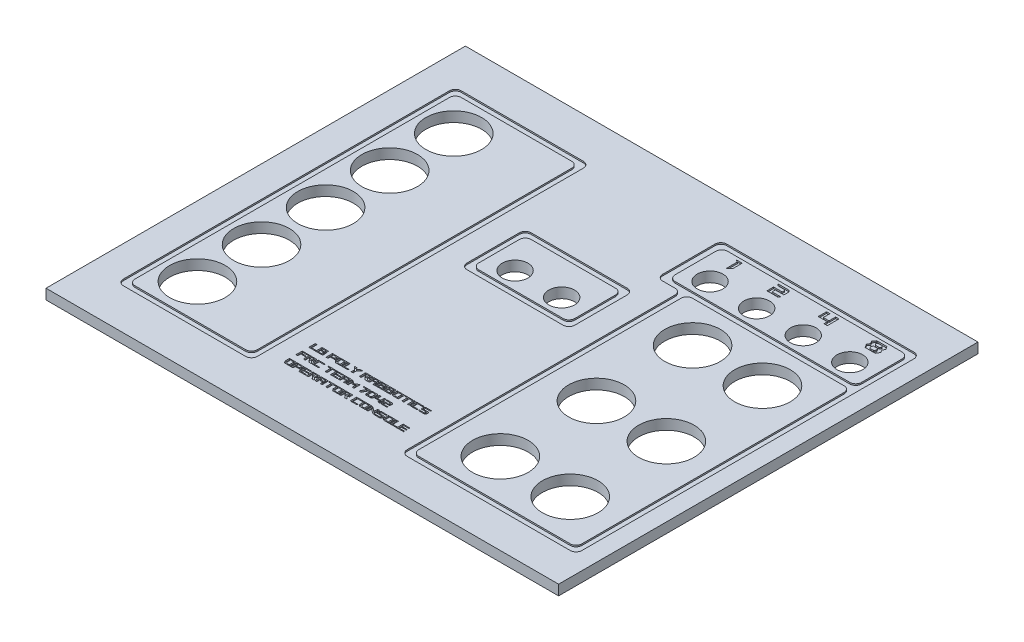
SolidWorks part; units mm, degrees
ref_plane "Front Plane" through (0, 0, 0) normal (0, 0, 1) x (1, 0, 0)
ref_plane "Top Plane" through (0, 0, 0) normal (0, 1, 0) x (1, 0, 0)
ref_plane "Right Plane" through (0, 0, 0) normal (1, 0, 0) x (0, 0, -1)
sketch "Sketch1" plane through (0, 0, 0) normal (0, 1, 0) x (1, 0, 0)
  line L1 (139.7, 114.3) -> (-139.7, 114.3)
  line L2 (139.7, 114.3) -> (139.7, -114.3)
  line L3 (139.7, -114.3) -> (-139.7, -114.3)
  line L4 (-139.7, 114.3) -> (-139.7, -114.3)
  line L5 (0, -114.3) -> (0, 114.3) construction
  line L6 (139.7, 0) -> (-139.7, 0) construction
  point P0 (0, 0)
  dimension "D1" = 279.4
  dimension "D2" = 228.6
extrude "Boss-Extrude1" add sketch "Sketch1" along normal blind 5.5562
sketch "Sketch2" plane through (0, 5.5562, 0) normal (0, 1, 0) x (1, 0, 0)
  line L1 (-139.7, 114.3) -> (-139.7, -114.3) construction
  circle A0 centre (-101.6, 69.85) radius 15.1606
  circle A3 centre (-101.6, 34.925) radius 15.1606
  circle A4 centre (-101.6, 0) radius 15.1606
  circle A5 centre (-101.6, -34.925) radius 15.1606
  circle A6 centre (-101.6, -69.85) radius 15.1606
  point P15 (-139.7, 0)
  dimension "D1" = 5
  dimension "D2" = 30.3213
  dimension "D3" = 34.925
  dimension "D4" = 38.1
extrude "Cut-Extrude1" cut sketch "Sketch2" against normal through all
sketch "Sketch3" plane through (0, 5.5562, 0) normal (0, 1, 0) x (1, 0, 0)
  line L0 (-101.6, 69.85) -> (38.1, 69.85) construction
  line L1 (-101.6, 34.925) -> (63.5, 34.925) construction
  line L2 (139.7, -114.3) -> (139.7, 114.3) construction
  line L3 (101.6, 34.925) -> (101.6, -17.4625) construction
  line L4 (-101.6, -85.0106) -> (63.5, -85.0106) construction
  circle A0 centre (38.1, 69.85) radius 7.0247
  circle A1 centre (63.5, 69.85) radius 7.0247
  circle A2 centre (88.9, 69.85) radius 7.0247
  circle A3 centre (114.3, 69.85) radius 7.0247
  circle A6 centre (63.5, 34.925) radius 15.1606
  circle A7 centre (101.6, 34.925) radius 15.1606
  circle A8 centre (-101.6, -69.85) radius 15.1606 construction
  circle A10 centre (101.6, -17.4625) radius 15.1606
  circle A11 centre (63.5, -17.4625) radius 15.1606
  circle A12 centre (101.6, -69.85) radius 15.1606
  circle A13 centre (63.5, -69.85) radius 15.1606
  dimension "D1" = 14.0494
  dimension "D5" = 38.1
  dimension "D6" = 30.3213
  dimension "D3" = 12.7
  dimension "D4" = 25.4
  dimension "D7" = 38.1
  dimension "D2" = 4
  dimension "D8" = 3
extrude "Cut-Extrude2" cut sketch "Sketch3" against normal through all
sketch "Sketch4" plane through (0, 5.5562, 0) normal (0, 1, 0) x (1, 0, 0)
  line L0 (-49.9269, -92.075) -> (-122.9519, -92.075)
  line L1 (-53.1019, -88.9) -> (-119.7769, -88.9)
  line L3 (-53.1019, 88.9) -> (-119.7769, 88.9)
  line L4 (-119.7769, -88.9) -> (-119.7769, 88.9)
  line L5 (-86.4394, 88.9) -> (-86.4394, -88.9) construction
  line L6 (-53.1019, 0) -> (-119.7769, 0) construction
  line L7 (-122.9519, -92.075) -> (-122.9519, 92.075)
  line L8 (-49.9269, 92.075) -> (-122.9519, 92.075)
  line L9 (-49.9269, -92.075) -> (-49.9269, 92.075)
  line L10 (38.1, 57.15) -> (127, -92.075) construction
  line L12 (38.1, 57.15) -> (38.1, -92.075)
  line L13 (38.1, -92.075) -> (127, -92.075)
  line L14 (127, 57.15) -> (127, -92.075)
  line L15 (63.5, -17.4625) -> (101.6, -17.4625) construction
  line L17 (130.175, 60.325) -> (130.175, -95.25)
  line L18 (34.925, -95.25) -> (130.175, -95.25)
  line L19 (34.925, 57.15) -> (34.925, -95.25)
  line L22 (127, 57.15) -> (38.1, 57.15)
  line L24 (127, 88.9) -> (127, 60.325)
  line L26 (-53.1019, 88.9) -> (-53.1019, -88.9)
  line L27 (-49.9269, -92.075) -> (-49.9269, 92.075) construction
  line L28 (-53.1019, -88.9) -> (-53.1019, 88.9) construction
  line L30 (34.925, 60.325) -> (34.925, -95.25) construction
  line L31 (34.925, 60.325) -> (130.175, 60.325) construction
  line L33 (34.925, 57.15) -> (21.7795, 57.15)
  line L34 (38.1, 57.15) -> (127, 57.15) construction
  line L35 (21.7795, 57.15) -> (21.7795, 92.075)
  line L36 (21.7795, 92.075) -> (130.175, 92.075)
  line L37 (127, 88.9) -> (25.4, 88.9)
  line L38 (25.4, 88.9) -> (25.4, 60.325)
  line L39 (25.4, 60.325) -> (127, 60.325)
  line L40 (130.175, 60.325) -> (130.175, 92.075)
  circle A0 centre (-101.6, 0) radius 15.1606 construction
  circle A1 centre (63.5, -17.4625) radius 15.1606 construction
  circle A2 centre (63.5, 69.85) radius 7.0247 construction
  circle A4 centre (38.1, 69.85) radius 7.0247 construction
  circle A5 centre (114.3, 69.85) radius 7.0247 construction
  point P0 (-86.4394, 0)
  point P20 (82.3396, -17.4625)
  point P23 (82.55, -17.4625)
  point P29 (82.55, -17.4625)
  dimension "D9" = 12.7
  dimension "D7" = 12.7
  dimension "D1" = 33.3375
  dimension "D2" = 88.9
  dimension "D4" = 12.7
  dimension "D5" = 3.175
  dimension "D6" = 88.9
  dimension "D8" = 3.6205
  dimension "D11" = 3.175
  dimension "D12" = 3.175
  dimension "D3" = 3.175
extrude "Cut-Extrude3" cut sketch "Sketch4" against normal blind 0.7937
fillet "Fillet1" radius 3.175 22 edges at (130.175, 5.1594, 95.25) (127, 5.1594, 92.075) (34.925, 5.1594, 95.25) (38.1, 5.1594, 92.075) (-119.7769, 5.1594, 88.9) (-122.9519, 5.1594, 92.075) (-49.9269, 5.1594, 92.075) (-53.1019, 5.1594, 88.9) (38.1, 5.1594, -57.15) (127, 5.1594, -57.15) (34.925, 5.1594, -57.15) (127, 5.1594, -60.325) (130.175, 5.1594, -92.075) (127, 5.1594, -88.9) (21.7795, 5.1594, -57.15) (25.4, 5.1594, -60.325) (21.7795, 5.1594, -92.075) (25.4, 5.1594, -88.9) (-49.9269, 5.1594, -92.075) (-53.1019, 5.1594, -88.9) (-122.9519, 5.1594, -92.075) (-119.7769, 5.1594, -88.9)
sketch "Sketch5" plane through (0, 5.5562, 0) normal (0, 1, 0) x (1, 0, 0)
  line L0 (-40.4019, -70.556) -> (27.4392, -70.556) construction
  line L1 (-49.9269, -88.9) -> (-49.9269, 88.9) construction
  text T0 "LB Poly Rabbotics\r\nFRC Team 7042\r\nOperator Console" font "ROG Fonts" height 3.5
  dimension "D1" = 9.525
extrude "Cut-Extrude4" cut sketch "Sketch5" against normal blind 0.7937
sketch "Sketch6" plane through (0, 5.5562, 0) normal (0, 1, 0) x (1, 0, 0)
  line L0 (32.0219, 80.9625) -> (119.1467, 80.9625) construction
  line L1 (123.825, 88.9) -> (28.575, 88.9) construction
  text T0 " 1       2       4       8" font "ROG Fonts" height 6.35
  dimension "D1" = 7.9375
extrude "Cut-Extrude5" cut sketch "Sketch6" against normal blind 0.7937
sketch "Sketch7" plane through (0, 5.5562, 0) normal (0, 1, 0) x (1, 0, 0)
  line L0 (-33.6947, 44.0928) -> (18.6928, 44.0928)
  line L1 (-30.5197, 40.9178) -> (15.5178, 40.9178)
  line L2 (-33.6947, 37.7428) -> (-33.6947, 15.5178)
  line L3 (-30.5197, 12.3428) -> (15.5178, 12.3428)
  line L4 (18.6928, 37.7428) -> (18.6928, 15.5178)
  line L5 (-7.5009, 12.3428) -> (-7.5009, 40.9178) construction
  line L6 (-33.6947, 26.6303) -> (18.6928, 26.6303) construction
  line L7 (21.8678, 40.9178) -> (21.8678, 12.3428)
  line L8 (-33.6947, 9.1678) -> (18.6928, 9.1678)
  line L9 (-36.8697, 40.9178) -> (-36.8697, 12.3428)
  line L10 (-36.8697, 31.8817) -> (-49.9269, 31.8817) construction
  line L11 (-49.9269, -88.9) -> (-49.9269, 88.9) construction
  line L12 (21.8678, 31.8817) -> (34.925, 31.8817) construction
  line L13 (34.925, 53.975) -> (34.925, -92.075) construction
  line L14 (-36.8697, 9.1678) -> (21.8678, 9.1678) construction
  line L15 (-36.8697, 44.0928) -> (-36.8697, 9.1678) construction
  line L16 (-33.6947, 40.9178) -> (-33.6947, 12.3428) construction
  line L17 (-33.6947, 12.3428) -> (18.6928, 12.3428) construction
  line L18 (21.8678, 44.0928) -> (21.8678, 9.1678) construction
  line L19 (18.6928, 40.9178) -> (18.6928, 12.3428) construction
  line L20 (-36.8697, 44.0928) -> (21.8678, 44.0928) construction
  line L21 (-33.6947, 40.9178) -> (18.6928, 40.9178) construction
  line L22 (24.9545, 57.15) -> (24.9545, 44.0928) construction
  arc A0 (-33.6947, 9.1678) -> (-36.8697, 12.3428) centre (-33.6947, 12.3428) cw
  arc A1 (-33.6947, 15.5178) -> (-30.5197, 12.3428) centre (-30.5197, 15.5178) ccw
  arc A2 (21.8678, 12.3428) -> (18.6928, 9.1678) centre (18.6928, 12.3428) cw
  arc A3 (15.5178, 12.3428) -> (18.6928, 15.5178) centre (15.5178, 15.5178) ccw
  arc A4 (18.6928, 44.0928) -> (21.8678, 40.9178) centre (18.6928, 40.9178) cw
  arc A5 (15.5178, 40.9178) -> (18.6928, 37.7428) centre (15.5178, 37.7428) cw
  arc A6 (-33.6947, 44.0928) -> (-36.8697, 40.9178) centre (-33.6947, 40.9178) ccw
  arc A7 (-30.5197, 40.9178) -> (-33.6947, 37.7428) centre (-30.5197, 37.7428) ccw
  point P0 (-7.5009, 26.6303)
  dimension "D2" = 3.175
  dimension "D1" = 3.175
  dimension "D3" = 28.575
  dimension "D4" = 26.1937
extrude "Cut-Extrude6" cut sketch "Sketch7" against normal blind 0.7937
sketch "Sketch8" plane through (0, 5.5562, 0) normal (0, 1, 0) x (1, 0, 0)
  line L0 (-7.5009, 12.3428) -> (-7.5009, 27.5264) construction
  line L1 (-30.5197, 12.3428) -> (15.5178, 12.3428) construction
  line L2 (-30.5197, 12.3428) -> (15.5178, 12.3428) construction
  circle A0 centre (-20.2009, 21.8678) radius 7.0247
  circle A1 centre (5.1991, 21.8678) radius 7.0247
  dimension "D1" = 14.0494
  dimension "D2" = 25.4
  dimension "D3" = 9.525
extrude "Cut-Extrude7" cut sketch "Sketch8" against normal through all
